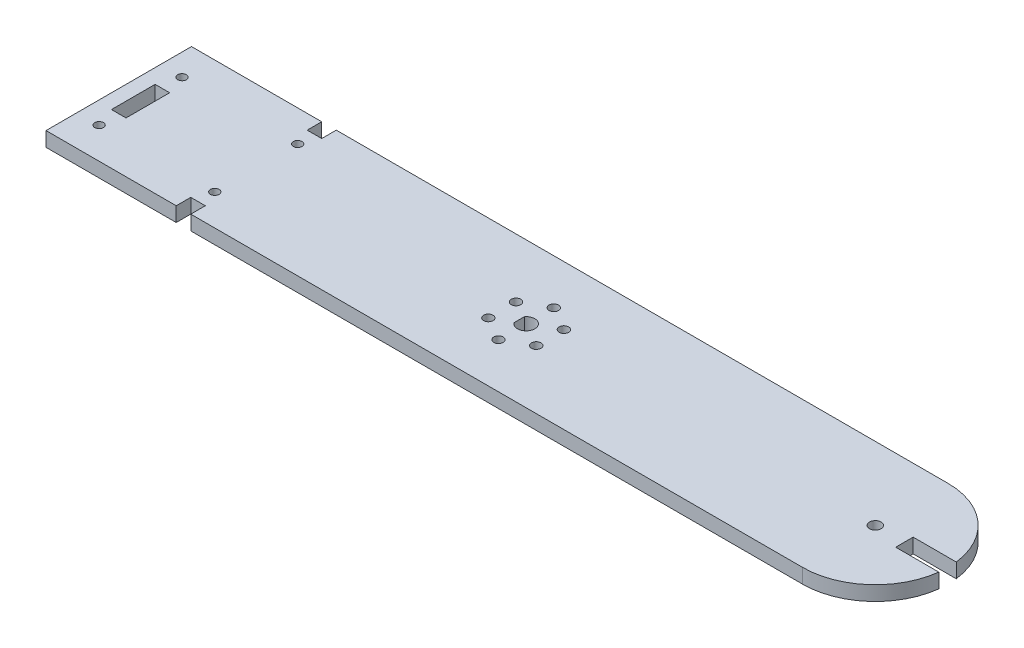
SolidWorks part; units mm, degrees
material "CA"
ref_plane "Alzado" through (0, 0, 0) normal (0, 0, 1) x (1, 0, 0)
ref_plane "Planta" through (0, 0, 0) normal (0, 1, 0) x (1, 0, 0)
ref_plane "Vista lateral" through (0, 0, 0) normal (1, 0, 0) x (0, 0, -1)
sketch "Croquis1" plane through (0, 0, 0) normal (0, 1, 0) x (1, 0, 0)
  line L0 (0, 0) -> (44.75, 0)
  line L1 (0, 0) -> (0, 50)
  line L2 (44.75, 0) -> (44.75, 5)
  line L3 (44.75, 5) -> (49.75, 5)
  line L4 (49.75, 5) -> (49.75, 0)
  line L5 (49.75, 50) -> (260, 50)
  line L6 (0, 50) -> (44.75, 50)
  line L7 (44.75, 50) -> (44.75, 45)
  line L8 (44.75, 45) -> (49.75, 45)
  line L9 (49.75, 45) -> (49.75, 50)
  line L10 (49.75, 0) -> (260, 0)
  line L11 (270, 22) -> (284.8193, 22)
  line L12 (5, 32.5) -> (5, 17.5)
  line L13 (137.6, 23.2) -> (137.6, 26.8)
  line L14 (5, 32.5) -> (10, 32.5)
  line L15 (10, 32.5) -> (10, 17.5)
  line L16 (5, 17.5) -> (10, 17.5)
  line L17 (5, 17.5) -> (4.923, 17.4659)
  line L19 (270, 22) -> (270, 28)
  line L20 (270, 28) -> (284.8193, 28)
  arc A0 (140, 50) -> (140, 0) centre (140, 25) cw construction
  circle A1 centre (47.25, 39.25) radius 1.5
  circle A2 centre (140, 34.5) radius 1.63
  arc A3 (137.6, 26.8) -> (137.6, 23.2) centre (140, 25) cw
  circle A4 centre (47.25, 10.75) radius 1.5
  circle A5 centre (7.5, 10.75) radius 1.5
  circle A6 centre (7.5, 39.25) radius 1.5
  arc A7 (260, 50) -> (284.8193, 28) centre (260, 25) cw
  circle A8 centre (131.7728, 29.75) radius 1.63
  circle A9 centre (131.7728, 20.25) radius 1.63
  circle A10 centre (140, 15.5) radius 1.63
  circle A11 centre (148.2272, 20.25) radius 1.63
  circle A12 centre (148.2272, 29.75) radius 1.63
  circle A13 centre (260, 25) radius 2
  arc A14 (284.8193, 22) -> (260, 0) centre (260, 25) cw
  point P34 (10, 0)
  point P46 (140, 25)
  dimension "D7" = 3
  dimension "D9" = 3.26
  dimension "D13" = 5
  dimension "D10" = 3
  dimension "D5" = 5
  dimension "D2" = 4
  dimension "D3" = 44.75
  dimension "D4" = 50
  dimension "D6" = 5
  dimension "D8" = 9.5
  dimension "D12" = 5
  dimension "D14" = 15
  dimension "D16" = 6
  dimension "D11" = 6
extrude "Saliente-Extruir1" add sketch "Croquis1" along normal blind 5 contours L1 L6 L7 L8 L9 L5 A7 L20 L19 L11 A14 L10 L4 L3 L2 L0 | L16 L15 L14 L12 | A6 | A4 | A1 | A5 | A3 L13 | A9 | A8 | A2 | A12 | A11 | A10 | A13
